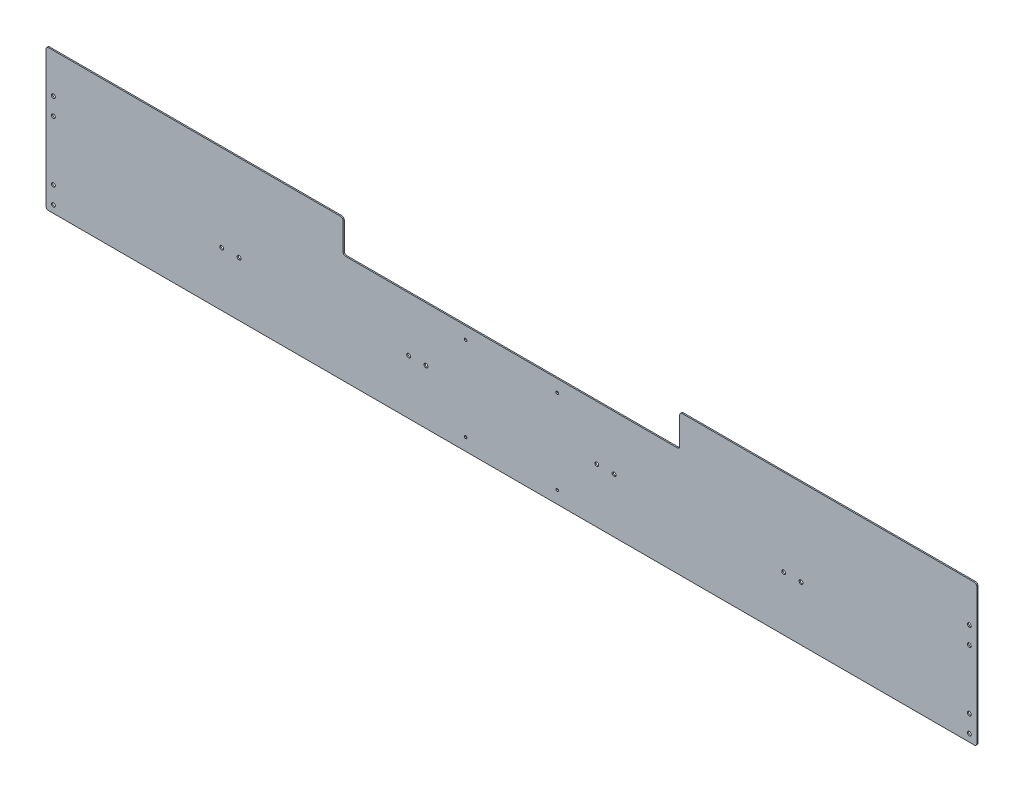
SolidWorks part; units mm, degrees
material "PC High Viscosity"
ref_plane "Front Plane" through (0, 0, 0) normal (0, 0, 1) x (1, 0, 0)
ref_plane "Top Plane" through (0, 0, 0) normal (0, 1, 0) x (1, 0, 0)
ref_plane "Right Plane" through (0, 0, 0) normal (1, 0, 0) x (0, 0, -1)
sketch "Sketch1" plane through (0, 0, 0) normal (0, 0, 1) x (1, 0, 0)
  line L0 (-431.8, 222.25) -> (-1193.8, 222.25)
  line L1 (-1193.8, -139.7) -> (1193.8, -139.7)
  line L2 (-1193.8, -139.7) -> (-1193.8, 139.7)
  line L4 (1193.8, -139.7) -> (1193.8, 139.7)
  line L5 (-1193.8, -139.7) -> (1193.8, 139.7) construction
  line L6 (-1193.8, 139.7) -> (1193.8, -139.7) construction
  line L8 (1193.8, 139.7) -> (1193.8, 222.25)
  line L9 (1193.8, 222.25) -> (431.8, 222.25)
  line L10 (-1193.8, 139.7) -> (-1193.8, 222.25)
  line L11 (0, 241.3) -> (0, 139.7) construction
  line L12 (1193.8, 180.975) -> (-1193.8, 180.975) construction
  line L14 (431.8, 222.25) -> (431.8, 139.7)
  line L16 (-431.8, 222.25) -> (-431.8, 139.7)
  line L17 (431.8, 222.25) -> (-431.8, 139.7) construction
  line L18 (431.8, 139.7) -> (-431.8, 222.25) construction
  line L19 (1193.8, 139.7) -> (431.8, 139.7) construction
  line L20 (-431.8, 139.7) -> (-1193.8, 139.7) construction
  line L21 (-431.8, 139.7) -> (431.8, 139.7)
  line L22 (-1193.8, 139.7) -> (1193.8, 139.7) construction
  point P0 (0, 0)
  point P9 (0, 180.975)
  point P196 (0, 180.975)
  dimension "D1" = 2387.6
  dimension "D2" = 279.4
  dimension "D3" = 82.55
  dimension "D4" = 863.6
extrude "Boss-Extrude1" add sketch "Sketch1" along normal mid plane 3.175
hole_wizard "25/64 (0.39063) Diameter Hole1" positions "Sketch2" profile "Sketch3" hole size "25/64" standard "ANSI Inch" end condition through all
sketch "Sketch2" plane through (0, 0, 1.5875) normal (0, 0, 1) x (1, 0, 0)
  line L5 (-1193.8, -139.7) -> (1193.8, -139.7) construction
  line L8 (-1193.8, 222.25) -> (-1193.8, -139.7) construction
  line L10 (-1193.8, 222.25) -> (-1193.8, -139.7) construction
  line L11 (-431.8, 139.7) -> (-1193.8, 139.7) construction
  line L12 (-1193.8, 222.25) -> (-1193.8, -139.7) construction
  line L13 (-1193.8, -139.7) -> (1193.8, -139.7) construction
  line L14 (0, -139.7) -> (0, 139.7) construction
  line L15 (431.8, 139.7) -> (-431.8, 139.7) construction
  point P0 (-1174.75, 120.65)
  point P2 (-1174.75, -120.65)
  point P4 (1174.75, 120.65)
  point P6 (1174.75, -120.65)
  point P12 (-742.95, 0)
  point P14 (-698.5, 0)
  point P60 (-263.525, 0)
  point P62 (-219.075, 0)
  point P64 (742.95, 0)
  point P65 (698.5, 0)
  point P66 (263.525, 0)
  point P67 (219.075, 0)
  point P68 (1174.75, -76.2)
  point P70 (1174.75, 76.2)
  point P72 (-1174.75, 76.2)
  point P74 (-1174.75, -76.2)
  dimension "D1" = 44.45
  dimension "D2" = 44.45
  dimension "D3" = 19.05
  dimension "D4" = 260.35
  dimension "D5" = 19.05
  dimension "D6" = 450.85
  dimension "D7" = 930.275
  dimension "D8" = 44.45
  dimension "D9" = 44.45
  dimension "D11" = 139.7
sketch "Sketch3" plane through (-1174.75, 120.65, 1.5875) normal (1, 0, 0) x (0, -1, 0)
  line L0 (0, 0) -> (0, 3.175)
  line L1 (0, 3.175) -> (4.961, 3.175)
  line L2 (4.961, 3.175) -> (4.961, 0)
  line L5 (4.961, 0) -> (0, 0)
  line L11 (0, -6.35) -> (0, 107.95) construction
  dimension "Thru Hole Dia." = 9.922
  dimension "Thru Hole Depth" = 3.175
fillet "Fillet1" radius 6.35 8 edges at (1193.8, -139.7, 0) (1193.8, 222.25, 0) (431.8, 222.25, 0) (431.8, 139.7, 0) (-431.8, 222.25, 0) (-431.8, 139.7, 0) (-1193.8, -139.7, 0) (-1193.8, 222.25, 0)
hole_wizard "1/4 Clearance Hole2" positions "Sketch6" profile "Sketch5" hole size "1/4" standard "ANSI Inch" end condition through all
sketch "Sketch6" plane through (0, 0, 1.5875) normal (0, 0, 1) x (1, 0, 0)
  line L1 (0, -139.7) -> (0, 139.7) construction
  line L2 (-1187.45, -139.7) -> (1187.45, -139.7) construction
  line L3 (425.45, 139.7) -> (-425.45, 139.7) construction
  line L12 (0, 0) -> (-268.486, 0) construction
  line L14 (0, 0) -> (268.486, 0) construction
  circle A1 centre (-263.525, 0) radius 4.961 construction
  circle A2 centre (263.525, 0) radius 4.961 construction
  point P0 (-117.475, 107.95)
  point P2 (-117.475, -107.95)
  point P4 (117.475, 107.95)
  point P6 (117.475, -107.95)
  dimension "D1" = 234.95
  dimension "D2" = 215.9
  dimension "D3" = 31.75
sketch "Sketch5" plane through (-117.475, 107.95, 1.5875) normal (1, 0, 0) x (0, -1, 0)
  line L0 (0, 0) -> (0, 3.175)
  line L1 (0, 3.175) -> (3.3782, 3.175)
  line L2 (3.3782, 3.175) -> (3.3782, 0)
  line L5 (3.3782, 0) -> (0, 0)
  line L11 (0, -6.35) -> (0, 107.95) construction
  dimension "Thru Hole Dia." = 6.7564
  dimension "Thru Hole Depth" = 3.175
hole_wizard "3/8 Clearance Hole1" positions "Sketch7" profile "Sketch8" hole size "3/8" standard "ANSI Inch"
sketch "Sketch7" plane through (0, 0, 1.5875) normal (0, 0, 1) x (1, 0, 0)
  line L2 (-117.475, -107.95) -> (117.475, -107.95) construction
  line L3 (-117.475, -107.95) -> (-117.475, 107.95) construction
  line L4 (-117.475, 107.95) -> (117.475, 107.95) construction
  line L5 (117.475, -107.95) -> (117.475, 107.95) construction
  line L6 (-117.475, -107.95) -> (117.475, 107.95) construction
  line L7 (-117.475, 107.95) -> (117.475, -107.95) construction
  line L9 (-117.475, 0) -> (117.475, 0) construction
  circle A0 centre (-117.475, -107.95) radius 3.3782 construction
  point P0 (-117.475, -114.3)
  point P176 (117.475, -114.3)
  point P189 (-117.475, 101.6)
  point P191 (117.475, 101.6)
  dimension "D1" = 6.35
  dimension "D2" = 6.35
sketch "Sketch8" plane through (-117.475, -114.3, 1.5875) normal (1, 0, 0) x (0, -1, 0)
  line L0 (0, 0) -> (0, 3.175)
  line L1 (0, 3.175) -> (5.0419, 3.175)
  line L2 (5.0419, 3.175) -> (5.0419, 0)
  line L5 (5.0419, 0) -> (0, 0)
  line L11 (0, -6.35) -> (0, 107.95) construction
  dimension "Thru Hole Dia." = 10.0838
  dimension "Thru Hole Depth" = 3.175
